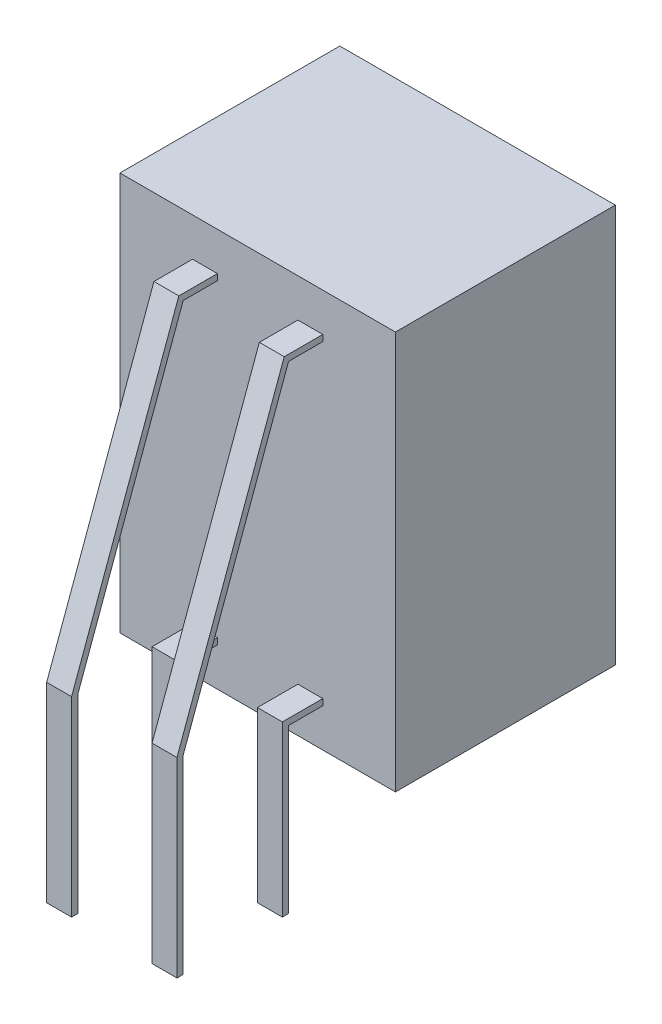
SolidWorks part; units mm, degrees
ref_plane "Front Plane" through (0, 0, 0) normal (0, 0, 1) x (1, 0, 0)
ref_plane "Top Plane" through (0, 0, 0) normal (0, 1, 0) x (1, 0, 0)
ref_plane "Right Plane" through (0, 0, 0) normal (1, 0, 0) x (0, 0, -1)
sketch "Sketch1" plane through (0, 0, 0) normal (0, 1, 0) x (1, 0, 0)
  line L1 (-3.32, 0) -> (3.32, 0)
  line L2 (-3.32, 0) -> (-3.32, -5.3)
  line L3 (-3.32, -5.3) -> (3.32, -5.3)
  line L4 (3.32, 0) -> (3.32, -5.3)
  point P4 (0, 0)
  dimension "D1" = 6.64
  dimension "D2" = 5.3
extrude "Boss-Extrude1" add sketch "Sketch1" along normal blind 9.6
sketch "Sketch2" plane through (0, 0, 0) normal (0, 0, -1) x (-1, 0, 0)
  line L0 (-3.32, 9.6) -> (3.32, 9.6) construction
  line L1 (-2.07, 6.6) -> (-0.47, 6.6)
  line L2 (-2.07, 6.6) -> (-2.07, 3)
  line L3 (-2.07, 3) -> (-0.47, 3)
  line L4 (-0.47, 6.6) -> (-0.47, 3)
  line L5 (0.47, 6.6) -> (2.07, 6.6)
  line L6 (0.47, 6.6) -> (0.47, 3)
  line L7 (0.47, 3) -> (2.07, 3)
  line L8 (2.07, 6.6) -> (2.07, 3)
  line L9 (-3.32, 9.6) -> (-3.32, 0) construction
  point P8 (2.07, 4.8)
  point P11 (-1.27, 6.6)
  dimension "D1" = 1.6
  dimension "D2" = 2.54
  dimension "D3" = 3.6
  dimension "D4" = 4.8
  dimension "D5" = 2.05
extrude "Cut-Extrude1" cut sketch "Sketch2" against normal blind 0.4
sketch "Sketch3" plane through (0, 0, 0.4) normal (0, 0, -1) x (-1, 0, 0)
  line L0 (-2.07, 6.6) -> (-2.07, 3) construction
  line L1 (-1.97, 4.7) -> (-0.57, 4.7)
  line L2 (-1.97, 4.7) -> (-1.97, 3.1)
  line L3 (-1.97, 3.1) -> (-0.57, 3.1)
  line L4 (-0.57, 4.7) -> (-0.57, 3.1)
  line L5 (0.57, 4.7) -> (1.97, 4.7)
  line L6 (0.57, 4.7) -> (0.57, 3.1)
  line L7 (0.57, 3.1) -> (1.97, 3.1)
  line L8 (1.97, 4.7) -> (1.97, 3.1)
  line L9 (-2.07, 3) -> (-0.47, 3) construction
  dimension "D1" = 1.4
  dimension "D2" = 1.6
  dimension "D3" = 0.1
  dimension "D4" = 0.1
  dimension "D5" = 2.54
extrude "Boss-Extrude3" add sketch "Sketch3" along normal offset from surface (1.4 mm away) 1 contours L4 L1 L2 L3 | L6 L5 L8 L7 up to face at (1.27, 4.8, 0) offset beyond the face yes
ref_plane "Plane4" through (1.27, 0, 0) normal (1, 0, 0) x (0, 0, -1)
sketch "Sketch4" plane through (1.27, 0, 0) normal (1, 0, 0) x (0, 0, -1)
  line L0 (-5.3, 8.675) -> (-6.2299, 8.675)
  line L1 (-5.3, 9.6) -> (-5.3, 0) construction
  line L2 (-6.2299, 8.675) -> (-8.815, 1.6016)
  line L3 (-8.815, 1.6016) -> (-8.815, -3)
  line L4 (-8.815, -3) -> (-8.665, -3)
  line L5 (-8.665, -3) -> (-8.665, 1.575)
  line L6 (-8.665, 1.575) -> (-6.125, 8.525)
  line L7 (-6.125, 8.525) -> (-5.3, 8.525)
  line L8 (-5.3, 8.525) -> (-5.3, 8.675)
  line L9 (-5.3, 0.925) -> (-6.125, 0.925)
  line L10 (-6.125, 0.925) -> (-6.125, -3)
  line L11 (-6.125, -3) -> (-6.275, -3)
  line L12 (-6.275, -3) -> (-6.275, 1.075)
  line L13 (-6.275, 1.075) -> (-5.3, 1.075)
  line L14 (-5.3, 1.075) -> (-5.3, 0.925)
  line L15 (0, 9.6) -> (0, 0) construction
  line L16 (-5.3, 0) -> (0, 0) construction
  line L17 (-5.3, 9.6) -> (0, 9.6) construction
  point P12 (-6.2, -3)
  point P21 (-5.3, 1)
  point P22 (-5.3, 8.6)
  point P25 (-7.2598, 8.525)
  point P26 (-8.74, -3)
  point P27 (-8.665, 1.3851)
  dimension "D1" = 6.2
  dimension "D2" = 3
  dimension "D3" = 0.15
  dimension "D4" = 0.15
  dimension "D5" = 1
  dimension "D6" = 1
  dimension "D7" = 0.15
  dimension "D8" = 0.15
  dimension "D9" = 0.15
  dimension "D10" = 2.54
  dimension "D11" = 0.5
extrude "Boss-Extrude4" add sketch "Sketch4" along normal mid plane 0.6 separate body
mirror "Mirror1" about plane through (0, 0, 0) normal (1, 0, 0) of "Boss-Extrude4"
